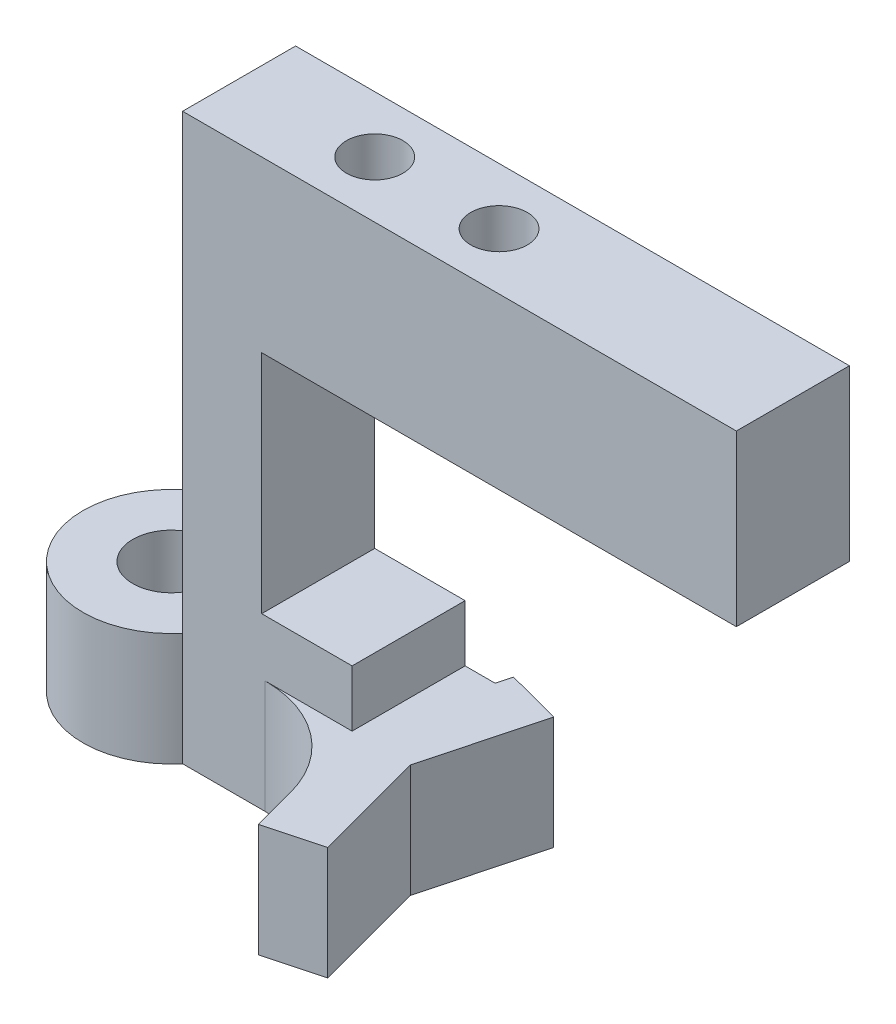
SolidWorks part; units mm, degrees
ref_plane "Front Plane" through (0, 0, 0) normal (0, 0, 1) x (1, 0, 0)
ref_plane "Top Plane" through (0, 0, 0) normal (0, 1, 0) x (1, 0, 0)
ref_plane "Right Plane" through (0, 0, 0) normal (1, 0, 0) x (0, 0, -1)
sketch "Sketch1" plane through (0, 0, 0) normal (0, 0, 1) x (1, 0, 0)
  line L0 (49, 0) -> (0, 0)
  line L1 (0, 0) -> (0, -50)
  line L2 (0, -50) -> (15, -50)
  line L3 (15, -50) -> (15, -15)
  line L4 (15, -15) -> (49, -15)
  line L5 (49, -15) -> (49, 0)
  dimension "D1" = 49
  dimension "D2" = 50
  dimension "D3" = 15
  dimension "D4" = 15
extrude "Boss-Extrude1" add sketch "Sketch1" along normal mid plane 10
sketch "Sketch2" plane through (0, -50, 0) normal (0, -1, 0) x (1, 0, 0)
  line L0 (18, -6.2846) -> (15, 5)
  line L1 (15, 5) -> (18, 16.2846)
  line L3 (15, 5) -> (25.3473, 5) construction
  line L4 (15, 5) -> (49, 5) construction
  line L5 (18, 16.2846) -> (22.8322, 15)
  line L6 (22.8322, 15) -> (20.1737, 5)
  line L7 (20.1737, 5) -> (22.8322, -5)
  line L8 (22.8322, -5) -> (18, -6.2846)
  line L9 (15, -5) -> (17.6585, -5)
  line L10 (15, -5) -> (49, -5) construction
  line M9 (15, -5) -> (15, 5)
  dimension "D1" = 5
  dimension "D2" = 3
extrude "Boss-Extrude2" add sketch "Sketch2" against normal blind 10 contours L8 L7 L6 L5 L1 L0 | L9 L0 M9 | L1 L3 L6 L5
fillet "Fillet1" radius 10 1 edges at (15, -45, 5)
sketch "Sketch3" plane through (0, 0, -5) normal (0, 0, -1) x (-1, 0, 0)
  line L0 (-7, 0) -> (-7, 22) construction
  line L1 (-15, -15) -> (-7, -15)
  line L2 (-15, -15) -> (-15, -35)
  line L3 (-15, -35) -> (-7, -35)
  line L4 (-7, -15) -> (-7, -35)
  dimension "D1" = 20
extrude "Cut-Extrude1" cut sketch "Sketch3" against normal through all
sketch "Sketch4" plane through (0, -15, 0) normal (0, -1, 0) x (1, 0, 0)
  circle A0 centre (23, 0) radius 2.5
  circle A1 centre (12, 0) radius 2.5
  dimension "D1" = 5
extrude "Cut-Extrude2" cut sketch "Sketch4" against normal through all
sketch "Sketch5" plane through (0, -50, 0) normal (0, -1, 0) x (1, 0, 0)
  line L1 (0, 5) -> (0, -5)
  circle A0 centre (-6, 0) radius 3.4
  arc A1 (0, 5) -> (0, -5) centre (-6, 0) ccw
  point P2 (0, 0)
  dimension "D1" = 6.8
  dimension "D2" = 6
extrude "Boss-Extrude4" add sketch "Sketch5" against normal blind 10
sketch "Sketch6" plane through (0, -40, 0) normal (0, 1, 0) x (1, 0, 0)
  circle A0 centre (-6, 0) radius 4
  dimension "D1" = 8
